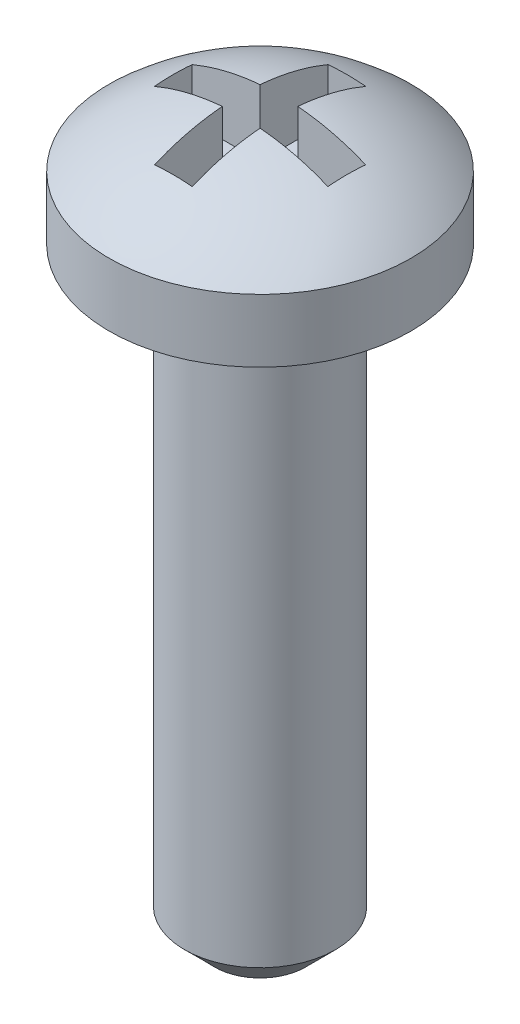
SolidWorks part; units mm, degrees
ref_plane "Front Plane" through (0, 0, 0) normal (0, 0, 1) x (1, 0, 0)
ref_plane "Top Plane" through (0, 0, 0) normal (0, 1, 0) x (1, 0, 0)
ref_plane "Right Plane" through (0, 0, 0) normal (1, 0, 0) x (0, 0, -1)
sketch "Sketch1" plane through (0, 0, 0) normal (0, 0, 1) x (1, 0, 0)
  line L0 (-2, 0) -> (-1, 0)
  line L1 (-1, 0) -> (-1, -7.6)
  line L2 (-1, -7.6) -> (-0.6, -8)
  line L3 (-0.6, -8) -> (0, -8)
  line L4 (0, -8) -> (0, 1.6)
  line L6 (-2, 2.9272) -> (-2, -0.4018) construction
  line L7 (-2, 0) -> (-2, 0.8361)
  line L8 (0, 1.6) -> (-2, 1.6) construction
  arc A0 (-2, 0.8361) -> (0, 1.6) centre (0, -1.4) cw
  dimension "D7" = 3
  dimension "D1" = 1
  dimension "D2" = 0.4
  dimension "D3" = 135
  dimension "D4" = 8
  dimension "D5" = 2
  dimension "D6" = 1.6
revolve "Revolve1" add sketch "Sketch1" angle 360 about L4
sketch "Sketch2" plane through (0, 0, 0) normal (0, -1, 0) x (1, 0, 0)
  line L0 (-0.25, 1.15) -> (0.25, -1.15) construction
  line L1 (-0.25, 1.15) -> (0.25, 1.15)
  line L2 (-0.25, 1.15) -> (-0.25, 0.25)
  line L3 (-0.25, -1.15) -> (0.25, -1.15)
  line L4 (0.25, 1.15) -> (0.25, 0.25)
  line L5 (-1.15, 0.25) -> (-0.25, 0.25)
  line L6 (-1.15, 0.25) -> (-1.15, -0.25)
  line L7 (-1.15, -0.25) -> (-0.25, -0.25)
  line L8 (1.15, 0.25) -> (1.15, -0.25)
  line L9 (-1.15, 0.25) -> (1.15, -0.25) construction
  line L10 (0.25, 0.25) -> (1.15, 0.25)
  line L11 (0.25, -0.25) -> (0.25, -1.15)
  line L12 (0.25, -0.25) -> (1.15, -0.25)
  line L13 (-0.25, -0.25) -> (-0.25, -1.15)
  dimension "D1" = 0.5
  dimension "D2" = 2.3
extrude "Cut-Extrude1" cut sketch "Sketch2" against normal through all from offset 0.7
